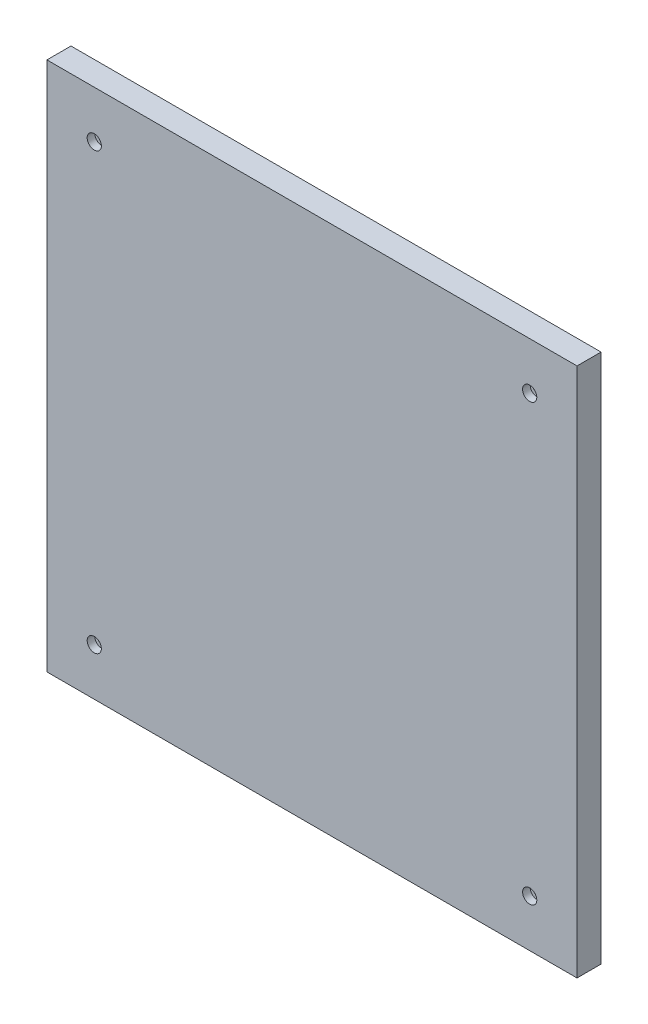
SolidWorks part; units mm, degrees
ref_plane "Front Plane" through (0, 0, 0) normal (0, 0, 1) x (1, 0, 0)
ref_plane "Top Plane" through (0, 0, 0) normal (0, 1, 0) x (1, 0, 0)
ref_plane "Right Plane" through (0, 0, 0) normal (1, 0, 0) x (0, 0, -1)
sketch "Sketch1" plane through (0, 0, 0) normal (0, 0, 1) x (1, 0, 0)
  line L1 (184.0657, 242.017) -> (464.0657, 242.017)
  line L2 (184.0657, 242.017) -> (184.0657, -37.983)
  line L3 (184.0657, -37.983) -> (464.0657, -37.983)
  line L4 (464.0657, 242.017) -> (464.0657, -37.983)
  circle A0 centre (209.0657, 217.017) radius 2
  circle A1 centre (439.0657, 217.017) radius 2
  circle A2 centre (439.0657, -12.983) radius 2
  circle A3 centre (209.0657, -12.983) radius 2
  dimension "D1" = 4
extrude "Boss-Extrude1" add sketch "Sketch1" along normal blind 12.7
sketch "Sketch2" plane through (0, 0, 12.7) normal (0, 0, 1) x (1, 0, 0)
  circle A0 centre (209.0657, -12.983) radius 3.75
  circle A1 centre (209.0657, 217.017) radius 3.75
  circle A2 centre (439.0657, 217.017) radius 3.75
  circle A3 centre (439.0657, -12.983) radius 3.75
  dimension "D1" = 7.5
extrude "Cut-Extrude1" cut sketch "Sketch2" against normal blind 4
equation "\"wood_thickness\"= 0.5in"
equation "\"D1@Boss-Extrude1\"=\"wood_thickness\""
